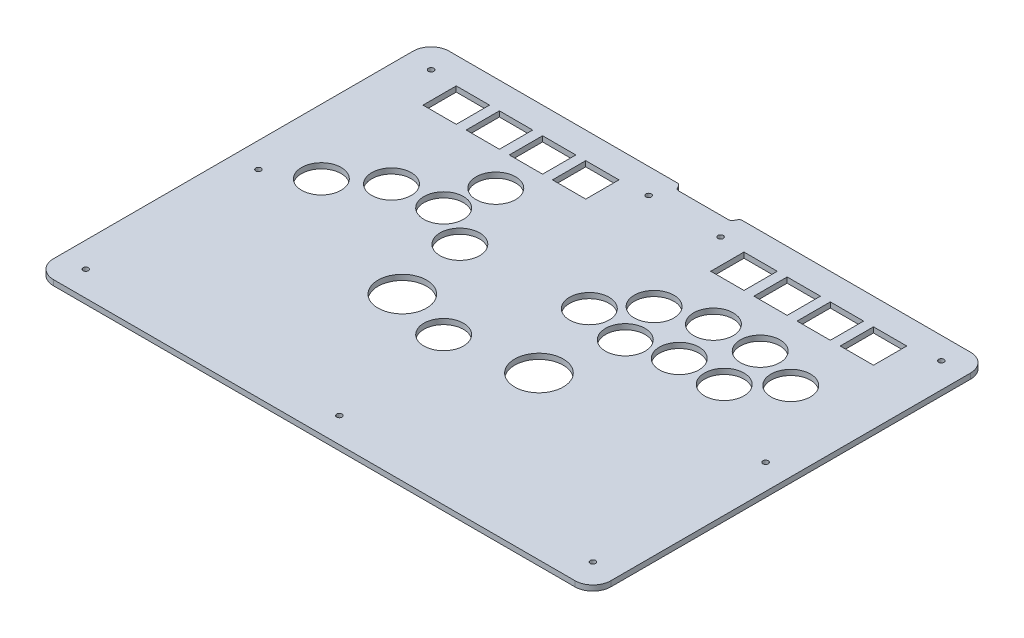
SolidWorks part; units mm, degrees
ref_plane "前视基准面" through (0, 0, 0) normal (0, 0, 1) x (1, 0, 0)
ref_plane "上视基准面" through (0, 0, 0) normal (0, 1, 0) x (1, 0, 0)
ref_plane "右视基准面" through (0, 0, 0) normal (1, 0, 0) x (0, 0, -1)
sketch "草图1" plane through (0, 0, 0) normal (0, 1, 0) x (1, 0, 0)
  line L1 (10, 0) -> (136.8844, 0)
  line L2 (0, -10) -> (0, -210)
  line L3 (10, -220) -> (300, -220)
  line L4 (310, -10) -> (310, -210)
  line L5 (28.75, -14.75) -> (47.25, -14.75)
  line L6 (28.75, -14.75) -> (28.75, -33.25)
  line L7 (28.75, -33.25) -> (47.25, -33.25)
  line L8 (173, -85) -> (173, 0) construction
  line L9 (173, -85) -> (310, -85) construction
  line L10 (190, -66) -> (190, 0) construction
  line L11 (215, -58) -> (215, 0) construction
  line L12 (241, -58) -> (241, 0) construction
  line L13 (247, -84) -> (247, 0) construction
  line L14 (222, -84) -> (222, 0) construction
  line L15 (0, -220) -> (310, 0) construction
  line L16 (241, -58) -> (310, -58) construction
  line L17 (247, -84) -> (310, -84) construction
  line L18 (215, -58) -> (310, -58) construction
  line L19 (222, -84) -> (310, -84) construction
  line L20 (190, -66) -> (310, -66) construction
  line L21 (310, -220) -> (0, 0) construction
  line L22 (141.1791, -3.5) -> (168.8209, -3.5)
  line L23 (139.4291, -2.4682) -> (138.6344, -1.0318)
  line L24 (170.5709, -2.4682) -> (171.3656, -1.0318)
  line L25 (173.1156, 0) -> (300, 0)
  line L26 (155, -110) -> (155, -220) construction
  line L27 (47.25, -14.75) -> (47.25, -33.25)
  line L28 (28.75, -14.75) -> (47.25, -33.25) construction
  line L29 (28.75, -33.25) -> (47.25, -14.75) construction
  line L30 (52.75, -14.75) -> (71.25, -14.75)
  line L31 (52.75, -14.75) -> (52.75, -33.25)
  line L32 (52.75, -33.25) -> (71.25, -33.25)
  line L33 (71.25, -14.75) -> (71.25, -33.25)
  line L34 (52.75, -14.75) -> (71.25, -33.25) construction
  line L35 (52.75, -33.25) -> (71.25, -14.75) construction
  line L36 (76.75, -14.75) -> (95.25, -14.75)
  line L37 (76.75, -14.75) -> (76.75, -33.25)
  line L38 (76.75, -33.25) -> (95.25, -33.25)
  line L39 (95.25, -14.75) -> (95.25, -33.25)
  line L40 (76.75, -14.75) -> (95.25, -33.25) construction
  line L41 (76.75, -33.25) -> (95.25, -14.75) construction
  line L42 (100.75, -14.75) -> (119.25, -14.75)
  line L43 (100.75, -14.75) -> (100.75, -33.25)
  line L44 (100.75, -33.25) -> (119.25, -33.25)
  line L45 (119.25, -14.75) -> (119.25, -33.25)
  line L46 (100.75, -14.75) -> (119.25, -33.25) construction
  line L47 (100.75, -33.25) -> (119.25, -14.75) construction
  line L48 (188.75, -14.75) -> (207.25, -14.75)
  line L49 (188.75, -14.75) -> (188.75, -33.25)
  line L50 (188.75, -33.25) -> (207.25, -33.25)
  line L51 (207.25, -14.75) -> (207.25, -33.25)
  line L52 (188.75, -14.75) -> (207.25, -33.25) construction
  line L53 (188.75, -33.25) -> (207.25, -14.75) construction
  line L54 (212.75, -14.75) -> (231.25, -14.75)
  line L55 (212.75, -14.75) -> (212.75, -33.25)
  line L56 (212.75, -33.25) -> (231.25, -33.25)
  line L57 (231.25, -14.75) -> (231.25, -33.25)
  line L58 (212.75, -14.75) -> (231.25, -33.25) construction
  line L59 (212.75, -33.25) -> (231.25, -14.75) construction
  line L60 (236.75, -14.75) -> (255.25, -14.75)
  line L61 (236.75, -14.75) -> (236.75, -33.25)
  line L62 (236.75, -33.25) -> (255.25, -33.25)
  line L63 (255.25, -14.75) -> (255.25, -33.25)
  line L64 (236.75, -14.75) -> (255.25, -33.25) construction
  line L65 (236.75, -33.25) -> (255.25, -14.75) construction
  line L66 (260.75, -14.75) -> (279.25, -14.75)
  line L67 (260.75, -14.75) -> (260.75, -33.25)
  line L68 (260.75, -33.25) -> (279.25, -33.25)
  line L69 (279.25, -14.75) -> (279.25, -33.25)
  line L70 (260.75, -14.75) -> (279.25, -33.25) construction
  line L71 (260.75, -33.25) -> (279.25, -14.75) construction
  arc A0 (10, 0) -> (0, -10) centre (10, -10) ccw
  arc A1 (0, -210) -> (10, -220) centre (10, -210) ccw
  arc A2 (300, -220) -> (310, -210) centre (300, -210) ccw
  arc A3 (300, 0) -> (310, -10) centre (300, -10) cw
  circle A8 centre (173, -85) radius 11
  circle A9 centre (190, -66) radius 11
  circle A11 centre (215, -58) radius 11
  circle A12 centre (222, -84) radius 11
  circle A13 centre (247, -84) radius 11
  circle A14 centre (241, -58) radius 11
  circle A15 centre (14, -14) radius 1.5
  circle A16 centre (14, -206) radius 1.5
  circle A17 centre (296, -206) radius 1.5
  circle A18 centre (296, -12.2857) radius 1.5
  arc A19 (173.1156, 0) -> (171.3656, -1.0318) centre (173.1156, -2) ccw
  arc A20 (170.5709, -2.4682) -> (168.8209, -3.5) centre (168.8209, -1.5) cw
  arc A21 (141.1791, -3.5) -> (139.4291, -2.4682) centre (141.1791, -1.5) cw
  arc A22 (136.8844, 0) -> (138.6344, -1.0318) centre (136.8844, -2) cw
  circle A24 centre (198, -90) radius 11
  circle A25 centre (114, -130) radius 13.5
  circle A26 centre (190, -130) radius 13.5
  circle A27 centre (155, -206) radius 1.5
  circle A28 centre (175, -14) radius 1.5
  circle A29 centre (145, -138) radius 11
  circle A30 centre (106, -90) radius 11
  circle A31 centre (84, -77) radius 11
  circle A32 centre (58, -80) radius 11
  circle A33 centre (36, -97) radius 11
  circle A34 centre (89, -53) radius 11
  circle A35 centre (266, -66) radius 11
  circle A36 centre (110, -24) radius 4.5 construction
  circle A37 centre (86, -24) radius 4.5 construction
  circle A38 centre (62, -24) radius 4.5 construction
  circle A39 centre (38, -24) radius 4.5 construction
  circle A40 centre (198, -24) radius 4.5 construction
  circle A41 centre (222, -24) radius 4.5 construction
  circle A42 centre (246, -24) radius 4.5 construction
  circle A43 centre (270, -24) radius 4.5 construction
  circle A48 centre (135, -14) radius 1.5
  circle A51 centre (296, -110) radius 1.5
  circle A52 centre (14, -110) radius 1.5
  point P8 (0, 0)
  point P12 (0, -220)
  point P15 (310, -220)
  point P18 (310, 0)
  point P70 (171.9365, 0)
  point P73 (170, -3.5)
  point P76 (140, -3.5)
  point P79 (138.0635, 0)
  dimension "D3" = 10
  dimension "D7" = 90
  dimension "D10" = 22
  dimension "D15" = 53
  dimension "D16" = 22
  dimension "D19" = 22
  dimension "D20" = 22
  dimension "D21" = 22
  dimension "D22" = 84
  dimension "D23" = 22
  dimension "D24" = 22
  dimension "D32" = 22
  dimension "D34" = 3
  dimension "D37" = 3
  dimension "D40" = 3
  dimension "D43" = 3
  dimension "D47" = 3.5
  dimension "D50" = 140
  dimension "D51" = 2
  dimension "D52" = 90
  dimension "D54" = 27
  dimension "D56" = 27
  dimension "D59" = 3
  dimension "D61" = 14
  dimension "D62" = 3
  dimension "D64" = 22
  dimension "D8" = 22
  dimension "D9" = 22
  dimension "D11" = 22
  dimension "D12" = 22
  dimension "D13" = 22
  dimension "D76" = 9
  dimension "D84" = 9
  dimension "D86" = 3
  dimension "D89" = 18.5
  dimension "D92" = 18.5
  dimension "D95" = 18.5
  dimension "D98" = 3
  dimension "D101" = 18.5
  dimension "D103" = 18.5
  dimension "D87" = 3
  dimension "D1" = 220
  dimension "D2" = 310
  dimension "D14" = 89
  dimension "D17" = 85
  dimension "D18" = 137
  dimension "D25" = 66
  dimension "D26" = 120
  dimension "D27" = 36
  dimension "D28" = 58
  dimension "D29" = 95
  dimension "D30" = 88
  dimension "D31" = 69
  dimension "D33" = 63
  dimension "D35" = 14
  dimension "D36" = 14
  dimension "D38" = 14
  dimension "D39" = 14
  dimension "D41" = 14
  dimension "D42" = 14
  dimension "D44" = 14
  dimension "D45" = 12.2857
  dimension "D46" = 4
  dimension "D48" = 30
  dimension "D49" = 4
  dimension "D53" = 112
  dimension "D55" = 114
  dimension "D57" = 90
  dimension "D58" = 120
  dimension "D60" = 14
  dimension "D63" = 135
  dimension "D65" = 82
  dimension "D66" = 145
  dimension "D67" = 97
  dimension "D68" = 80
  dimension "D69" = 58
  dimension "D70" = 84
  dimension "D71" = 77
  dimension "D72" = 90
  dimension "D73" = 106
  dimension "D74" = 44
  dimension "D75" = 66
  dimension "D78" = 24
  dimension "D79" = 110
  dimension "D80" = 24
  dimension "D82" = 24
  dimension "D83" = 24
  dimension "D85" = 40
  dimension "D88" = 18.5
  dimension "D90" = 18.5
  dimension "D91" = 18.5
  dimension "D93" = 18.5
  dimension "D94" = 18.5
  dimension "D96" = 18.5
  dimension "D97" = 18.5
  dimension "D99" = 14
  dimension "D100" = 135
  dimension "D102" = 18.5
  dimension "D104" = 18.5
  dimension "D105" = 18.5
  dimension "D106" = 18.5
  dimension "D77" = 4
  dimension "D81" = 4
extrude "凸台-拉伸1" add sketch "草图1" along normal blind 3
